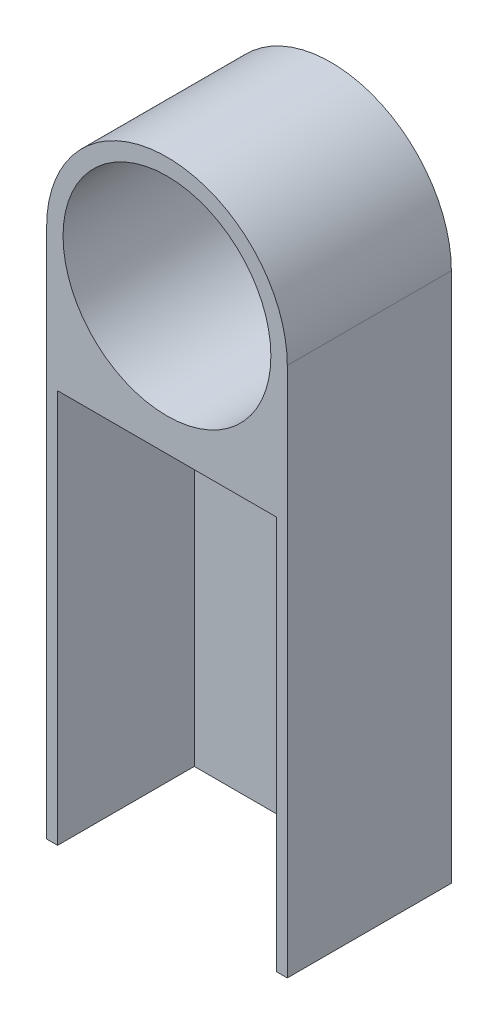
SolidWorks part; units mm, degrees
ref_plane "Front Plane" through (0, 0, 0) normal (0, 0, 1) x (1, 0, 0)
ref_plane "Top Plane" through (0, 0, 0) normal (0, 1, 0) x (1, 0, 0)
ref_plane "Right Plane" through (0, 0, 0) normal (1, 0, 0) x (0, 0, -1)
sketch "Sketch1" plane through (0, 0, 0) normal (0, 0, 1) x (1, 0, 0)
  line L0 (22, 0) -> (22, -110)
  line L1 (22, -110) -> (-22, -110)
  line L2 (-22, -110) -> (-22, 0)
  circle A0 centre (0, 0) radius 19
  circle A1 centre (0, 0) radius 22
  dimension "D1" = 38
  dimension "D2" = 44
  dimension "D3" = 110
extrude "Boss-Extrude1" add sketch "Sketch1" along normal blind 30 contours A1 A0 | A1 L2 L1 L0
sketch "Sketch2" plane through (0, 0, 30) normal (0, 0, 1) x (1, 0, 0)
  line L0 (20, -95) -> (-20, -95)
  line L1 (-20, -95) -> (-20, -25)
  line L2 (-20, -25) -> (20, -25)
  line L3 (20, -25) -> (20, -95)
  line L5 (22, 0) -> (22, -110) construction
  circle A0 centre (0, 0) radius 19 construction
  dimension "D2" = 25
  dimension "D1" = 70
  dimension "D3" = 40
  dimension "D4" = 2
extrude "Cut-Extrude1" cut sketch "Sketch2" against normal blind 25
sketch "Sketch3" plane through (0, 0, 30) normal (0, 0, 1) x (1, 0, 0)
  line L0 (-22, -97) -> (22, -97)
  line L1 (-22, -110) -> (-22, 0) construction
  line L2 (22, 0) -> (22, -110) construction
  line L3 (22, -97) -> (22, -110)
  line L4 (22, -110) -> (-22, -110) construction
  line L5 (22, -110) -> (-22, -110)
  line L6 (-22, -110) -> (-22, -97)
  line L7 (-20, -95) -> (20, -95) construction
  dimension "D1" = 2
extrude "Cut-Extrude2" cut sketch "Sketch3" against normal through all
sketch "Sketch4" plane through (0, -95, 0) normal (0, 1, 0) x (1, 0, 0)
  line L0 (-20, -5) -> (20, -5)
  line L1 (-20, -5) -> (20, -5) construction
  line L2 (20, -5) -> (20, -30) construction
  line L3 (20, -5) -> (20, -30)
  line L4 (20, -30) -> (-20, -30)
  line L5 (-20, -30) -> (-20, -5)
extrude "Cut-Extrude3" cut sketch "Sketch4" against normal blind 25
